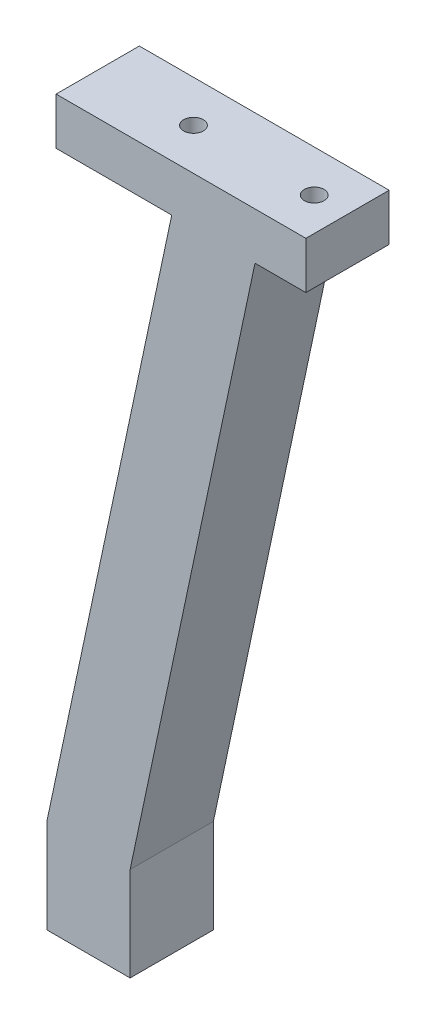
SolidWorks part; units mm, degrees
ref_plane "Front Plane" through (0, 0, 0) normal (0, 0, 1) x (1, 0, 0)
ref_plane "Top Plane" through (0, 0, 0) normal (0, 1, 0) x (1, 0, 0)
ref_plane "Right Plane" through (0, 0, 0) normal (1, 0, 0) x (0, 0, -1)
sketch "Sketch1" plane through (0, 0, 0) normal (0, 1, 0) x (1, 0, 0)
  line L1 (-10.9004, 9.3986) -> (7.0996, 9.3986)
  line L2 (-10.9004, 9.3986) -> (-10.9004, -8.6014)
  line L3 (-10.9004, -8.6014) -> (7.0996, -8.6014)
  line L4 (7.0996, 9.3986) -> (7.0996, -8.6014)
  dimension "D1" = 18
sketch "Sketch2" plane through (0, 0, 0) normal (0, 0, 1) x (1, 0, 0)
  line L0 (-10.9004, 0) -> (16.0943, 127) construction
  line L1 (-10.9004, 0) -> (7.0996, 0) construction
  line L2 (-10.9004, 0) -> (7.0996, 0) construction
  line L3 (-10.9004, 0) -> (16.0943, 127)
  dimension "D1" = 127
  dimension "D2" = 78
sweep "Sweep1" add profiles "Sketch1" path "Sketch2"
sketch "Sketch3" plane through (0, 127, 0) normal (0, 1, 0) x (1, 0, 0)
  line L0 (34.0943, 9.3986) -> (16.0943, 9.3986) construction
  line L1 (-8.9057, 9.3986) -> (45.0943, 9.3986)
  line L2 (-8.9057, 9.3986) -> (-8.9057, -8.6014)
  line L3 (-8.9057, -8.6014) -> (45.0943, -8.6014)
  line L4 (45.0943, 9.3986) -> (45.0943, -8.6014)
  line L5 (16.0943, -8.6014) -> (34.0943, -8.6014) construction
  line L6 (16.0943, 9.3986) -> (16.0943, -8.6014) construction
  dimension "D1" = 25
  dimension "D2" = 11
extrude "Boss-Extrude1" add sketch "Sketch3" along normal blind 10.16
sketch "Sketch4" plane through (0, 0, 0) normal (0, -1, 0) x (1, 0, 0)
  line L0 (-10.9004, 8.6014) -> (7.0996, 8.6014) construction
  line L1 (-5.9004, 3.6014) -> (2.0996, 3.6014)
  line L2 (-5.9004, 3.6014) -> (-5.9004, -4.3986)
  line L3 (-5.9004, -4.3986) -> (2.0996, -4.3986)
  line L4 (2.0996, 3.6014) -> (2.0996, -4.3986)
  line L5 (7.0996, 8.6014) -> (7.0996, -9.3986) construction
  line L6 (7.0996, -9.3986) -> (-10.9004, -9.3986) construction
  line L7 (-10.9004, -9.3986) -> (-10.9004, 8.6014) construction
  point P4 (-1.9004, 8.6014)
  dimension "D1" = 5
  dimension "D2" = 5
  dimension "D3" = 5
  dimension "D4" = 5
sketch "Sketch5" plane through (0, 0, 8.6014) normal (0, 0, 1) x (1, 0, 0)
  line L0 (-5.9004, 0) -> (9.9425, 74.5348)
  line L1 (-5.9004, 0) -> (2.0996, 0) construction
  line L2 (16.0943, 127) -> (-10.9004, 0) construction
  dimension "D1" = 76.2
sweep "Cut-Sweep1" cut profiles "Sketch4" path "Sketch5"
sketch "Sketch6" plane through (0, 127, 0) normal (0, -1, 0) x (1, 0, 0)
  line L0 (-8.9057, -0.3986) -> (45.0943, -0.3986) construction
  line L1 (-8.9057, -9.3986) -> (-8.9057, 8.6014) construction
  line L2 (45.0943, 8.6014) -> (45.0943, -9.3986) construction
  circle A0 centre (37.8943, -0.3986) radius 2.125
  circle A1 centre (11.7943, -0.3986) radius 2.125
  dimension "D1" = 4.25
  dimension "D2" = 26.1
  dimension "D3" = 7.2
extrude "Cut-Extrude1" cut sketch "Sketch6" against normal through all
sketch "Sketch7" plane through (0, 127, 0) normal (0, -1, 0) x (1, 0, 0)
  circle A0 centre (11.7943, -0.3986) radius 3.3
  circle A1 centre (37.8943, -0.3986) radius 3.3
  circle A2 centre (11.7943, -0.3986) radius 2.125 construction
  circle A4 centre (37.8943, -0.3986) radius 2.125 construction
  dimension "D1" = 6.6
extrude "Cut-Extrude2" cut sketch "Sketch7" against normal blind 3
sketch "Sketch8" plane through (-10.4292, 2.2168, 0) normal (-0.9781, 0.2079, 0) x (0, 0, 1)
  line L0 (-9.3986, 127.5709) -> (8.6014, 127.5709) construction
  line L1 (1.6014, 127.5709) -> (-2.3986, 127.5709)
  line L2 (1.6014, 127.5709) -> (1.6014, 107.5709)
  line L3 (1.6014, 107.5709) -> (-2.3986, 107.5709)
  line L4 (-2.3986, 127.5709) -> (-2.3986, 107.5709)
  line L5 (-0.3986, -2.2663) -> (-0.3986, 127.5709) construction
  line L6 (-9.3986, -2.2663) -> (8.6014, -2.2663) construction
  dimension "D1" = 20
  dimension "D2" = 4
extrude "Cut-Extrude3" cut sketch "Sketch8" against normal blind 2
sketch "Sketch9" plane through (0, 0, 0) normal (0, -1, 0) x (1, 0, 0)
  line L0 (-10.9004, 8.6014) -> (7.0996, 8.6014) construction
  line L1 (-10.9004, 8.6014) -> (7.0996, 8.6014)
  line L2 (-10.9004, 8.6014) -> (-10.9004, -9.3986)
  line L3 (-10.9004, -9.3986) -> (7.0996, -9.3986)
  line L4 (7.0996, 8.6014) -> (7.0996, -9.3986)
  line L5 (-10.9004, -9.3986) -> (-10.9004, 8.6014) construction
  line L6 (7.0996, -9.3986) -> (-10.9004, -9.3986) construction
  line L7 (7.0996, 8.6014) -> (7.0996, -9.3986) construction
extrude "Boss-Extrude2" add sketch "Sketch9" along normal blind 20.32
sketch "Sketch10" plane through (0, -20.32, 0) normal (0, -1, 0) x (1, 0, 0)
  line L0 (-10.9004, -0.3986) -> (7.0996, -0.3986) construction
  line L1 (-10.9004, 8.6014) -> (-10.9004, -9.3986) construction
  line L2 (7.0996, -9.3986) -> (7.0996, 8.6014) construction
  line L3 (-1.9004, 8.6014) -> (-1.9004, -9.3986) construction
  line L4 (7.0996, 8.6014) -> (-10.9004, 8.6014) construction
  line L5 (-10.9004, -9.3986) -> (7.0996, -9.3986) construction
  circle A0 centre (-1.9004, -0.3986) radius 1.6764
  dimension "D1" = 3.3528
extrude "Cut-Extrude4" cut sketch "Sketch10" against normal blind 15.24
